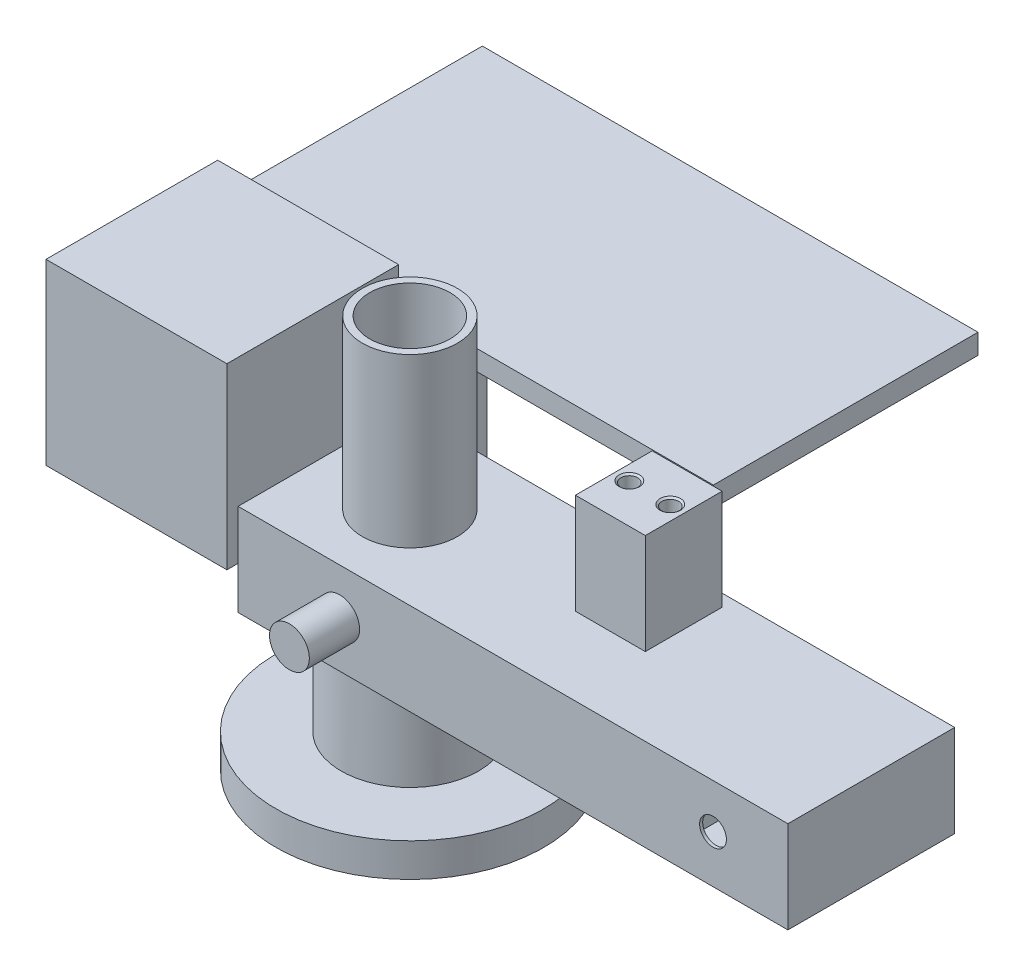
SolidWorks part; units mm, degrees
ref_plane "前基準面" through (0, 0, 0) normal (0, 0, 1) x (1, 0, 0)
ref_plane "上基準面" through (0, 0, 0) normal (0, 1, 0) x (1, 0, 0)
ref_plane "右基準面" through (0, 0, 0) normal (1, 0, 0) x (0, 0, -1)
sketch "草圖1" plane through (0, 0, 0) normal (0, 1, 0) x (1, 0, 0)
  line L1 (-30.3038, 12.448) -> (30.3038, 12.448)
  line L2 (-30.3038, 12.448) -> (-30.3038, -12.448)
  line L3 (-30.3038, -12.448) -> (30.3038, -12.448)
  line L4 (30.3038, 12.448) -> (30.3038, -12.448)
  line L5 (-30.3038, 12.448) -> (30.3038, -12.448) construction
  line L6 (-30.3038, -12.448) -> (30.3038, 12.448) construction
  point P0 (0, 0)
extrude "填料-伸長1" add sketch "草圖1" along normal blind 13.7304
sketch "草圖2" plane through (0, 0, 12.448) normal (0, 0, 1) x (1, 0, 0)
  line L6 (11.75, 12.75) -> (24.25, 12.75)
  line L7 (11.75, 12.75) -> (11.75, 2.25)
  line L8 (11.75, 2.25) -> (24.25, 2.25)
  line L9 (24.25, 12.75) -> (24.25, 2.25)
  line L10 (11.75, 12.75) -> (24.25, 2.25) construction
  line L11 (11.75, 2.25) -> (24.25, 12.75) construction
  point P10 (18, 7.5)
  dimension "D1" = 10.5
  dimension "D2" = 12.5
extrude "除料-伸長1" cut sketch "草圖2" against normal through all
sketch "草圖3" plane through (0, 0, 12.448) normal (0, 0, 1) x (1, 0, 0)
  line L0 (24.25, 2.25) -> (24.25, 12.75) construction
  line L1 (11.75, 12.75) -> (24.25, 12.75)
  line L2 (11.75, 12.75) -> (11.75, 2.25)
  line L3 (11.75, 2.25) -> (24.25, 2.25)
  line L4 (24.25, 12.75) -> (24.25, 2.25)
  line L5 (11.75, 12.75) -> (24.25, 2.25) construction
  line L6 (11.75, 2.25) -> (24.25, 12.75) construction
  line L7 (11.75, 2.25) -> (24.25, 2.25) construction
  point P0 (18, 7.5)
extrude "填料-伸長2" add sketch "草圖3" against normal blind 0.5
sketch "草圖4" plane through (0, 0, 11.948) normal (0, 0, -1) x (-1, 0, 0)
  circle A0 centre (-18, 7.5) radius 2
extrude "除料-伸長2" cut sketch "草圖4" against normal through all
sketch "草圖5" plane through (0, 0, 12.448) normal (0, 0, 1) x (1, 0, 0)
  circle A0 centre (-15.1519, 6.9) radius 2.975
extrude "填料-伸長3" add sketch "草圖5" along normal blind 7.5
sketch "草圖10" plane through (0, 13.7304, 0) normal (0, 1, 0) x (1, 0, 0)
  line L5 (8.4266, 10.6185) -> (18.8582, 10.6185)
  line L6 (8.4266, 10.6185) -> (8.4266, -0.8383)
  line L7 (8.4266, -0.8383) -> (18.8582, -0.8383)
  line L8 (18.8582, 10.6185) -> (18.8582, -0.8383)
  line L9 (8.4266, 10.6185) -> (18.8582, -0.8383) construction
  line L10 (8.4266, -0.8383) -> (18.8582, 10.6185) construction
  point P0 (13.6424, 4.8901)
extrude "填料-伸長4" add sketch "草圖10" along normal blind 15
sketch "草圖14" plane through (0, 0, 12.448) normal (0, 0, 1) x (1, 0, 0)
  circle A0 centre (18, 7.5) radius 2.8505
  circle A1 centre (18, 7.5) radius 2
extrude "填料-伸長5" add sketch "草圖14" along normal blind 1.5
sketch "草圖16" plane through (0, 0, 0) normal (0, -1, 0) x (1, 0, 0)
  circle A0 centre (-17.1174, 0) radius 5.5
  circle A1 centre (-17.1174, 0) radius 7.5
extrude "填料-伸長6" add sketch "草圖16" along normal blind 15
sketch "草圖17" plane through (0, -15, 0) normal (0, -1, 0) x (1, 0, 0)
  circle A0 centre (-17.1174, 0) radius 9.15
  circle A1 centre (-17.1174, 0) radius 17.05
extrude "填料-伸長7" add sketch "草圖17" along normal blind 5 separate body
sketch "草圖18" plane through (0, -15, 0) normal (0, 1, 0) x (1, 0, 0)
  circle A0 centre (-17.1174, 0) radius 10.2514
extrude "填料-伸長8" add sketch "草圖18" along normal blind 15
sketch "草圖19" plane through (0, -15, 0) normal (0, -1, 0) x (1, 0, 0)
  circle A0 centre (-17.1174, 0) radius 6
extrude "除料-伸長3" cut sketch "草圖19" against normal through all
sketch "草圖20" plane through (0, -20, 0) normal (0, -1, 0) x (1, 0, 0)
  line L1 (-27.7874, 1.565) -> (-27.7874, -1.565)
  line L2 (-27.7874, 1.565) -> (-26.1326, 1.565)
  line L3 (-27.7874, -1.565) -> (-26.1326, -1.565)
  line L4 (-26.1326, 1.565) -> (-26.1326, -1.565)
  circle A0 centre (-17.1174, 0) radius 9.15 construction
  point P7 (-27.7874, 0)
extrude "除料-伸長4" cut sketch "草圖20" against normal blind 15
sketch "草圖21" plane through (0, -15, 0) normal (0, -1, 0) x (1, 0, 0)
  line L0 (-26.1326, 1.565) -> (-25.7373, 1.565)
  line L1 (-26.1326, -1.565) -> (-25.7373, -1.565)
  line L2 (-25.7373, -1.565) -> (-25.7373, 1.565)
  line L3 (-26.1326, 1.565) -> (-26.1326, -1.565)
extrude "除料-伸長5" cut sketch "草圖21" against normal blind 10
sketch "草圖22" plane through (0, -15, 0) normal (0, 1, 0) x (1, 0, 0)
  circle A0 centre (-17.1174, 0) radius 19.9648
extrude "除料-伸長6" cut sketch "草圖22" against normal blind 10
sketch "草圖47" plane through (0, -15, 0) normal (0, -1, 0) x (1, 0, 0)
  circle A0 centre (-17.1174, 0) radius 20
extrude "填料-伸長16" add sketch "草圖47" along normal blind 5
sketch "草圖48" plane through (0, -15, 0) normal (0, 1, 0) x (1, 0, 0)
  circle A0 centre (-17.1174, 0) radius 6
extrude "除料-伸長21" cut sketch "草圖48" against normal blind 5
sketch "草圖49" plane through (0, -20, 0) normal (0, -1, 0) x (1, 0, 0)
  circle A0 centre (-17.1174, 0) radius 17.3
  circle A1 centre (-17.1174, 0) radius 14.8
extrude "除料-伸長22" cut sketch "草圖49" against normal blind 3
sketch "草圖50" plane through (0, -20, 0) normal (0, -1, 0) x (1, 0, 0)
  circle A0 centre (-17.1174, 0) radius 18.5909
  arc A1 (-2.1064, 10.9677) -> (0.2479, 6.6384) centre (-17.1174, 0) cw
  circle A2 centre (-17.1174, 0) radius 8.4841
sketch "草圖51" plane through (0, -20, 0) normal (0, -1, 0) x (1, 0, 0)
  line L0 (-3.1487, 10.2061) -> (-2.1064, 10.9677)
  line L1 (-0.958, 6.1775) -> (0.2479, 6.6384)
  line L2 (-15.2631, -17.2003) -> (-15.1247, -18.4838)
  line L3 (-19.8473, -17.0833) -> (-20.051, -18.358)
  line L4 (-32.9405, 6.9942) -> (-34.1213, 7.5161)
  line L5 (-30.547, 10.9058) -> (-31.5491, 11.7196)
  arc A0 (-3.1487, 10.2061) -> (-0.958, 6.1775) centre (-17.1174, 0) cw
  circle A1 centre (-17.1174, 0) radius 17.3 construction
  arc A2 (-15.1247, -18.4838) -> (-20.051, -18.358) centre (-17.1174, 0) cw
  arc A3 (-2.1064, 10.9677) -> (0.2479, 6.6384) centre (-17.1174, 0) cw
  arc A4 (-15.2631, -17.2003) -> (-19.8473, -17.0833) centre (-17.1174, 0) cw
  arc A5 (-34.1213, 7.5161) -> (-31.5491, 11.7196) centre (-17.1174, 0) cw
  arc A6 (-32.9405, 6.9942) -> (-30.547, 10.9058) centre (-17.1174, 0) cw
  point P23 (-17.1174, 0)
  dimension "D1" = 3
extrude "除料-伸長23" cut sketch "草圖51" against normal blind 3
sketch "草圖52" plane through (0, -17, 0) normal (0, -1, 0) x (1, 0, 0)
  circle A0 centre (-17.1174, 0) radius 18.5909
extrude "除料-伸長24" cut sketch "草圖52" along normal blind 2.3
sketch "草圖43" plane through (0, 0, 0) normal (0, -1, 0) x (1, 0, 0)
  line L0 (-30.3038, 14.126) -> (-30.3038, -14.126)
  line L1 (-57.3038, -14.126) -> (-57.3038, 14.126)
  line L2 (-30.3038, -14.126) -> (-57.3038, -14.126)
  line L3 (-57.3038, 14.126) -> (-30.3038, 14.126)
  line L6 (-55.9538, 12.15) -> (-31.6538, 12.15)
  line L7 (-55.9538, 12.15) -> (-55.9538, -12.15)
  line L8 (-55.9538, -12.15) -> (-31.6538, -12.15)
  line L9 (-31.6538, 12.15) -> (-31.6538, -12.15)
  line L10 (-55.9538, 12.15) -> (-31.6538, -12.15) construction
  line L11 (-55.9538, -12.15) -> (-31.6538, 12.15) construction
  point P3 (-30.3038, 0)
  point P7 (-43.8038, 0)
  dimension "D1" = 27
  dimension "D2" = 24.3
  dimension "D3" = 24.3
extrude "填料-伸長14" add sketch "草圖43" against normal blind 10
sketch "草圖53" plane through (0, -20, 0) normal (0, -1, 0) x (1, 0, 0)
  line L0 (-21.4684, 18.0746) -> (-18.5217, 5.8334)
  line L1 (-12.8881, 18.1034) -> (-15.7525, 5.8427)
  line L2 (0.7111, -5.2692) -> (-11.3635, -1.7006)
  line L3 (-3.5541, -12.7145) -> (-12.74, -4.1034)
  line L4 (-30.595, -12.8054) -> (-21.4672, -4.1328)
  line L5 (-34.9102, -5.389) -> (-22.8598, -1.7392)
  circle A1 centre (-17.1174, 0) radius 18.5909 construction
  circle A2 centre (-17.1174, 0) radius 6 construction
  arc A3 (-15.7525, 5.8427) -> (-18.5217, 5.8334) centre (-17.1174, 0) ccw
  arc A4 (-21.4684, 18.0746) -> (-12.8881, 18.1034) centre (-17.1174, 0) cw
  arc A5 (0.7111, -5.2692) -> (-3.5541, -12.7145) centre (-17.1174, 0) cw
  arc A6 (-12.74, -4.1034) -> (-11.3635, -1.7006) centre (-17.1174, 0) ccw
  arc A7 (-30.595, -12.8054) -> (-34.9102, -5.389) centre (-17.1174, 0) cw
  arc A8 (-22.8598, -1.7392) -> (-21.4672, -4.1328) centre (-17.1174, 0) ccw
  point P20 (-17.1174, 0)
  dimension "D1" = 3
extrude "填料-伸長17" add sketch "草圖53" against normal blind 5
sketch "草圖54" plane through (0, -20, 0) normal (0, -1, 0) x (1, 0, 0)
  circle A0 centre (-17.1174, 0) radius 14.8
  circle A1 centre (-17.1174, 0) radius 6
extrude "填料-伸長18" add sketch "草圖54" against normal blind 5
sketch "草圖56" plane through (30.3038, 0, 0) normal (1, 0, 0) x (0, 0, -1)
  line L0 (14.126, 10) -> (14.126, 0)
  line L1 (14.126, 0) -> (12.448, 0)
  line L2 (12.448, 0) -> (12.448, 10)
  line L3 (14.126, 10) -> (12.448, 10) construction
  line L4 (12.448, 10) -> (14.126, 10)
extrude "填料-伸長19" add sketch "草圖56" against normal blind 80
sketch "草圖57" plane through (0, 0, -12.448) normal (0, 0, -1) x (-1, 0, 0)
  line L0 (-24.25, 12.75) -> (-11.75, 12.75)
  line L1 (-11.75, 12.75) -> (-11.75, 0.75)
  line L2 (-24.25, 12.75) -> (-24.25, 0.75)
  line L3 (-24.25, 0.75) -> (-11.75, 0.75)
extrude "除料-伸長28" cut sketch "草圖57" along normal blind 80
sketch "草圖58" plane through (30.3038, 0, 0) normal (1, 0, 0) x (0, 0, -1)
  line L0 (12.448, 10) -> (14.126, 10)
  line L1 (14.126, 10) -> (14.126, 0)
  line L2 (14.126, 0) -> (12.448, 0)
  line L3 (12.448, 0) -> (12.448, 10)
extrude "除料-伸長29" cut sketch "草圖58" against normal blind 18.5
sketch "草圖59" plane through (0, 0, -14.126) normal (0, 0, -1) x (-1, 0, 0)
  line L0 (-11.75, 10) -> (-11.75, 43)
  line L1 (-11.75, 10) -> (-6.75, 10)
  line L2 (57.3038, 10) -> (-11.75, 10) construction
  line L3 (-6.75, 10) -> (-6.75, 43)
  line L4 (-6.75, 43) -> (-11.75, 43)
  line L5 (57.3038, 10) -> (57.3038, 43)
  line L6 (57.3038, 43) -> (52.3038, 43)
  line L7 (52.3038, 43) -> (52.3038, 0)
  line L8 (57.3038, 0) -> (-11.8038, 0) construction
  line L9 (52.3038, 0) -> (57.3038, 0)
  line L10 (19.7432, 0) -> (19.7432, 43)
  line L11 (19.7432, 43) -> (24.7432, 43)
  line L12 (24.7432, 43) -> (24.7432, 0)
  line L13 (24.7432, 0) -> (19.7432, 0)
  line M14 (57.3038, 10) -> (-11.75, 10)
  dimension "D1" = 5
  dimension "D2" = 5
  dimension "D3" = 5
extrude "填料-伸長21" add sketch "草圖59" against normal blind 2.621 contours L3 L4 L0 M14 | L12 L11 L10 M14 | L6 L7 L5 M14
sketch "草圖60" plane through (-57.3038, 0, 0) normal (-1, 0, 0) x (0, 0, 1)
  line L0 (-14.126, 43) -> (-39.126, 43)
  line L1 (-39.126, 43) -> (-39.126, 38.9382)
  line L3 (-11.5051, 10) -> (-11.5051, 43) construction
  line L4 (-39.126, 38.9382) -> (-14.126, 38.9382)
  line L5 (-14.126, 38.9382) -> (-14.126, 43)
  line L10 (-14.126, 0) -> (14.126, 0)
  line L11 (14.126, 0) -> (14.126, 10)
  line L12 (14.126, 10) -> (-11.5051, 10)
  line L13 (-11.5051, 10) -> (-11.5051, 43)
  line L14 (-11.5051, 43) -> (-14.126, 43)
  line L15 (-14.126, 43) -> (-14.126, 0)
  line L16 (-14.126, 0) -> (14.126, 0)
  line L17 (14.126, 0) -> (14.126, 10)
  line L18 (14.126, 10) -> (-11.5051, 10)
  line L19 (-11.5051, 10) -> (-11.5051, 38.9382)
  line L21 (-14.126, 43) -> (-14.126, 0)
  line M12 (-14.126, 43) -> (-14.126, 0)
  dimension "D1" = 0
extrude "填料-伸長22" add sketch "草圖60" against normal blind 69.2 contours L1 L4 L0 M12
sketch "草圖61" plane through (0, 43, 0) normal (0, 1, 0) x (1, 0, 0)
  line L0 (6.75, 14.126) -> (6.75, 34.126)
  line L1 (-19.7432, 14.126) -> (-19.7432, 34.126)
  line L2 (-19.7432, 34.126) -> (6.75, 34.126)
  line L3 (-24.7432, 14.126) -> (-24.7432, 34.126)
  line L4 (-52.3038, 14.126) -> (-52.3038, 34.126)
  line L5 (-52.3038, 34.126) -> (-24.7432, 34.126)
  line L6 (-52.3038, 14.126) -> (-24.7432, 14.126)
  line L7 (-19.7432, 14.126) -> (6.75, 14.126)
extrude "除料-伸長30" cut sketch "草圖61" against normal blind 5.2
sketch "草圖62" plane through (0, 38.9382, 0) normal (0, -1, 0) x (1, 0, 0)
  line L0 (-57.3038, -39.126) -> (11.8962, -39.126)
  line L1 (-52.3038, -34.126) -> (11.8962, -34.126)
  line L2 (11.8962, -39.126) -> (11.8962, -14.126) construction
  line L3 (11.8962, -34.126) -> (11.8962, -39.126)
  line L4 (-57.3038, -39.126) -> (-57.3038, -34.126)
  line L5 (-57.3038, -39.126) -> (-57.3038, -14.126) construction
  line L6 (-57.3038, -34.126) -> (-52.3038, -34.126)
sketch "草圖68" plane through (0, 0, -34.126) normal (0, 0, 1) x (1, 0, 0)
  line L0 (-65.7613, 43) -> (20.2387, 43)
  line L2 (20.2387, 43) -> (20.2387, 28)
  line L3 (20.2387, 28) -> (-65.7613, 28)
  line L4 (-65.7613, 28) -> (-65.7613, 43)
  point P3 (-22.7613, 43)
  dimension "D1" = 86
extrude "填料-伸長25" add sketch "草圖68" against normal blind 3
sketch "草圖69" plane through (0, 0, -39.126) normal (0, 0, -1) x (-1, 0, 0)
  line L0 (-11.8962, 43) -> (-11.8962, 38.9382)
  line L1 (-11.8962, 38.9382) -> (57.3038, 38.9382)
  line L2 (57.3038, 38.9382) -> (57.3038, 43)
  line L3 (57.3038, 43) -> (-11.8962, 43)
extrude "除料-伸長34" cut sketch "草圖69" against normal blind 2
sketch "草圖70" plane through (20.2387, 0, 0) normal (1, 0, 0) x (0, 0, -1)
  line L0 (37.126, 28) -> (37.126, 43)
  line L1 (37.126, 43) -> (14.126, 43)
  line L2 (14.126, 43) -> (14.126, 28)
  line L3 (14.126, 38.9382) -> (14.126, 0.75) construction
  line L4 (14.126, 28) -> (37.126, 28)
extrude "填料-伸長27" add sketch "草圖70" along normal blind 2
sketch "草圖71" plane through (-65.7613, 0, 0) normal (-1, 0, 0) x (0, 0, 1)
  line L0 (-37.126, 28) -> (-14.126, 28)
  line L1 (-14.126, 28) -> (-14.126, 43)
  line L2 (-11.5051, 43) -> (-34.126, 43) construction
  line L3 (-14.126, 43) -> (-14.126, 28) construction
  line L4 (-14.126, 43) -> (-37.126, 43)
  line L5 (-37.126, 43) -> (-37.126, 28)
extrude "填料-伸長28" add sketch "草圖71" along normal blind 2
sketch "草圖72" plane through (-57.3038, 0, 0) normal (-1, 0, 0) x (0, 0, 1)
  line L0 (-14.126, 43) -> (-11.5051, 43)
  line L1 (-11.5051, 43) -> (-11.5051, 27.998)
  line L2 (-11.5051, 10) -> (-11.5051, 43) construction
  line L3 (-11.5051, 27.998) -> (-14.126, 28)
  line L4 (-14.126, 28) -> (-14.126, 43)
extrude "填料-伸長29" add sketch "草圖72" along normal blind 10.5
sketch "草圖73" plane through (11.75, 0, 0) normal (1, 0, 0) x (0, 0, -1)
  line L0 (11.5051, 27.998) -> (14.126, 28)
  line L1 (14.126, 28) -> (14.126, 43)
  line L2 (14.126, 43) -> (11.5051, 43)
  line L3 (11.5051, 43) -> (11.5051, 27.998)
extrude "填料-伸長30" add sketch "草圖73" along normal blind 10.5
sketch "草圖74" plane through (0, 10, 0) normal (0, -1, 0) x (1, 0, 0)
  line L0 (-52.3038, -11.5051) -> (-55.9538, -11.5051)
  line L1 (-55.9538, -11.5051) -> (-55.9538, -12.15)
  line L2 (-55.9538, -12.15) -> (-52.3038, -12.15)
  line L3 (-52.3038, -12.15) -> (-52.3038, -11.5051)
extrude "除料-伸長35" cut sketch "草圖74" against normal through all
sketch "草圖76" plane through (13.6424, 28.7304, -0.3792) normal (0, 1, 0) x (1, 0, 0)
  line L0 (-3.0568, 4.6706) -> (3.0568, 4.6706)
  point P1 (3.0568, 4.6706)
  point P2 (-3.0568, 4.6706)
  point P3 (0, 4.6706)
hole_wizard "M3 螺紋孔1" positions "草圖80" profile "草圖82" tap size "M3" standard "ISO"
sketch "草圖80" plane through (0, 28.7304, 0) normal (0, 1, 0) x (1, 0, 0)
  point P0 (10.5856, 5.0498)
  point P3 (16.6992, 5.0498)
sketch "草圖82" plane through (10.5856, 28.7304, -5.0498) normal (1, 0, 0) x (0, 0, 1)
  line L0 (0, 0) -> (0, 15.7511)
  line L1 (0, 15.7511) -> (1.25, 15)
  line L2 (1.25, 15) -> (1.25, 0.2308)
  line L3 (1.25, 0.2308) -> (1.525, 0)
  line L5 (1.525, 0) -> (0, 0)
  line L6 (-1.25, 0.2308) -> (-1.525, 0) construction
  line L10 (0, 15.7511) -> (-1.25, 15) construction
  line L11 (0, -6.35) -> (0, 107.95) construction
  dimension "螺孔鑽直徑" = 2.5
  dimension "螺孔鑽深度" = 15
  dimension "近端錐孔直徑" = 3.05
  dimension "近端錐孔角度" = 100
  dimension "導頭角度" = 118
cosmetic thread "鑽孔螺紋1" parameters "D1"=2.7, "D2"=3
cosmetic thread "鑽孔螺紋2" parameters "D1"=2.7, "D2"=3
sketch "草圖83" plane through (-67.7613, 0, 0) normal (-1, 0, 0) x (0, 0, 1)
  line L0 (-37.126, 43) -> (-37.126, 28)
  line L1 (-37.126, 28) -> (-11.5051, 27.998)
  line L2 (-11.5051, 27.998) -> (-11.5051, 43)
  line L3 (-11.5051, 43) -> (-37.126, 43)
extrude "除料-伸長36" cut sketch "草圖83" against normal through all
sketch "草圖84" plane through (-67.8038, 0, 0) normal (-1, 0, 0) x (0, 0, 1)
  line L0 (-18.2068, 44.5992) -> (-5.6417, 43.5029)
  line L1 (-5.6417, 43.5029) -> (-11.5051, 27.998)
  line L2 (-11.5051, 27.998) -> (-14.126, 27.9982)
  line L3 (-14.126, 27.9982) -> (-18.2068, 44.5992)
extrude "除料-伸長37" cut sketch "草圖84" against normal through all
sketch "草圖85" plane through (0, 27.9971, 0.0022) normal (0, 1, 0.0001) x (1, 0, 0)
  line L0 (11.75, 11.5062) -> (-57.3038, 11.5059)
  line L1 (-57.3038, 11.5059) -> (-57.3038, 46.7116)
  line L2 (-57.3038, 46.7116) -> (11.7499, 46.7116)
  line L3 (11.7499, 46.7116) -> (11.75, 11.5062)
sketch "草圖87" plane through (0, 13.7304, 0) normal (0, 1, 0) x (1, 0, 0)
  circle A0 centre (-17.1174, 0) radius 7.0952
  circle A1 centre (-17.1174, 0) radius 6
extrude "填料-伸長32" add sketch "草圖87" along normal blind 25
sketch "草圖88" plane through (0, 27.9971, 0.0022) normal (0, 1, 0.0001) x (1, 0, 0)
  line L0 (-57.3038, 11.5059) -> (16.6752, 11.5059)
  line L1 (16.6752, 11.5059) -> (16.6752, 51.0037)
  line L2 (16.6752, 51.0037) -> (-57.3038, 51.0037)
  line L3 (-57.3038, 51.0037) -> (-57.3038, 11.5059)
extrude "填料-伸長33" add sketch "草圖88" against normal blind 3
sketch "草圖89" plane through (11.75, 0, 0) normal (1, 0, 0) x (0, 0, -1)
  line L0 (-12.448, 13.7304) -> (12.448, 13.7304)
  line L1 (12.448, 13.7304) -> (12.448, 0)
  line L2 (12.448, 0) -> (-12.448, 0)
  line L3 (-12.448, 0) -> (-12.448, 13.7304)
extrude "填料-伸長34" add sketch "草圖89" along normal blind 40
sketch "草圖90" plane through (0, 0, 12.448) normal (0, 0, 1) x (1, 0, 0)
  circle A0 centre (18, 7.5) radius 3.7574
extrude "除料-伸長38" cut sketch "草圖90" along normal through all
sketch "草圖91" plane through (0, 0, -12.448) normal (0, 0, -1) x (-1, 0, 0)
  line L0 (-46.8224, 12.3625) -> (-46.8224, 1.8625)
  line L1 (-46.8224, 1.8625) -> (-34.3224, 1.8625)
  line L2 (-46.8224, 12.3625) -> (-34.3224, 12.3625)
  line L3 (-34.3224, 12.3625) -> (-34.3224, 1.8625)
extrude "除料-伸長39" cut sketch "草圖91" against normal through all
sketch "草圖92" plane through (34.3224, 0, 0) normal (1, 0, 0) x (0, 0, -1)
  line L0 (-12.448, 12.3625) -> (-11.9894, 12.3625)
  line L1 (-11.9894, 12.3625) -> (-11.9894, 1.2188)
  line L2 (-11.9894, 1.2188) -> (-12.448, 1.2188)
  line L3 (-12.448, 10) -> (-12.448, 0) construction
  line L4 (-12.448, 1.2188) -> (-12.448, 12.3625)
extrude "填料-伸長35" add sketch "草圖92" along normal blind 15
sketch "草圖93" plane through (0, 0, 11.9894) normal (0, 0, -1) x (-1, 0, 0)
  circle A0 centre (-40.5724, 7.1125) radius 2
extrude "除料-伸長40" cut sketch "草圖93" against normal through all
sketch "草圖94" plane through (0, 0, 12.448) normal (0, 0, 1) x (1, 0, 0)
  circle A0 centre (40.5724, 7.1125) radius 23
  dimension "D1" = 46
sketch "草圖95" plane through (0, 10, 0) normal (0, 1, 0) x (1, 0, 0)
  line L0 (-57.3038, 11.5037) -> (-57.3038, -14.126)
  line L1 (-57.3038, -14.126) -> (-30.3038, -14.126)
  line L2 (-30.3038, -14.126) -> (-30.3038, 11.5038)
  line L3 (11.75, 11.504) -> (-57.3038, 11.5037) construction
  line L4 (-30.3038, 11.5038) -> (-57.3038, 11.5037)
  line L5 (-55.9538, 11.5051) -> (-55.9538, -12.15)
  line L6 (-55.9538, -12.15) -> (-31.6538, -12.15)
  line L7 (-31.6538, -12.15) -> (-31.6538, 12.15)
  line M3 (-31.6538, 12.15) -> (-31.6538, -12.15)
  line M4 (-31.6538, -12.15) -> (-55.9538, -12.15)
  line M5 (-55.9538, -12.15) -> (-55.9538, 11.5051)
  line M7 (-57.3038, 11.5051) -> (-57.3038, -14.126)
  line M8 (-57.3038, -14.126) -> (-30.3038, -14.126)
  line M9 (-30.3038, -14.126) -> (-30.3038, -12.448)
  line M10 (-30.3038, -12.448) -> (-30.3038, 12.448)
extrude "填料-伸長36" add sketch "草圖95" along normal blind 20 contours L4 M10 M3 M4 M5 M7 M8 M9
sketch "草圖96" plane through (0, 0, 14.126) normal (0, 0, 1) x (1, 0, 0)
  line L0 (-57.3038, 0) -> (-30.3038, 0)
  line L1 (-30.3038, 0) -> (-30.3038, 6.3579)
  line L2 (-30.3038, 30) -> (-30.3038, 0) construction
  line L3 (-30.3038, 6.3579) -> (-57.3038, 6.3579)
  line L4 (-57.3038, 30) -> (-57.3038, 0) construction
  line L5 (-57.3038, 6.3579) -> (-57.3038, 0)
extrude "除料-伸長41" cut sketch "草圖96" against normal through all
sketch "草圖97" plane through (0, 30, 0) normal (0, 1, 0) x (1, 0, 0)
  line L0 (-57.3038, 11.5037) -> (-30.3038, 11.5037)
  line L1 (-30.3038, 11.5037) -> (-30.3038, -14.126)
  line L2 (-30.3038, -14.126) -> (-57.3038, -14.126)
  line L3 (-57.3038, -14.126) -> (-57.3038, 11.5037)
extrude "填料-伸長37" add sketch "草圖97" along normal blind 3
